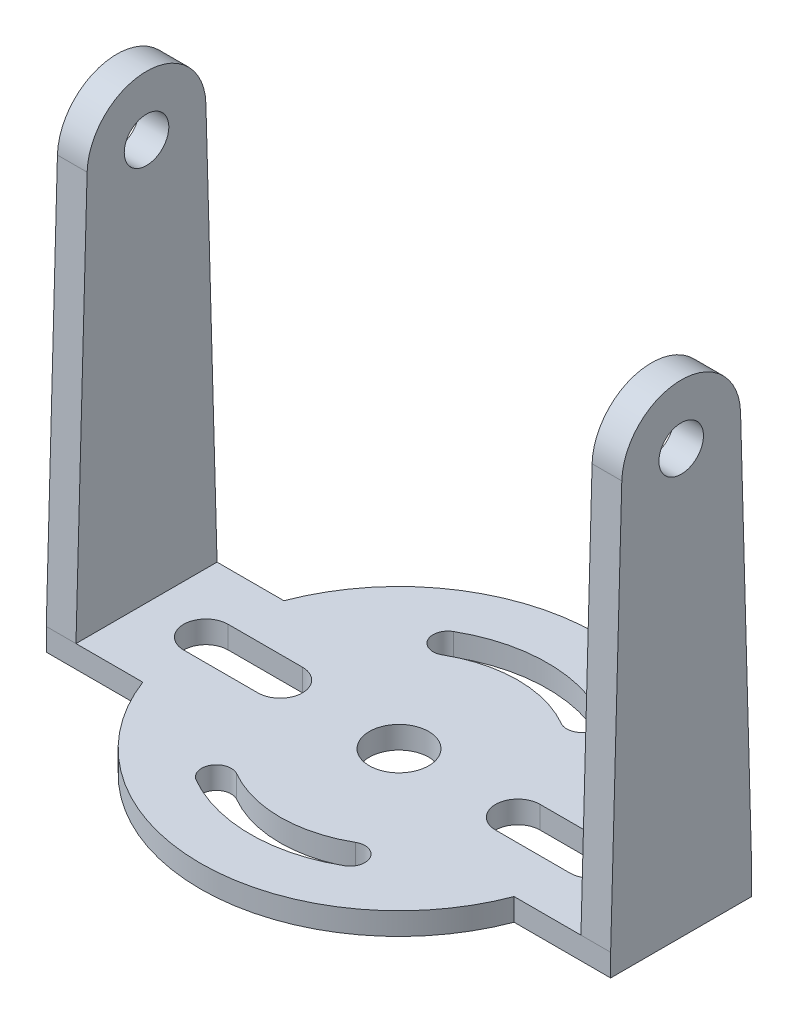
SolidWorks part; units mm, degrees
ref_plane "前视基准面" through (0, 0, 0) normal (0, 0, 1) x (1, 0, 0)
ref_plane "上视基准面" through (0, 0, 0) normal (0, 1, 0) x (1, 0, 0)
ref_plane "右视基准面" through (0, 0, 0) normal (1, 0, 0) x (0, 0, -1)
other "Configuration Table"
sketch "草图1" plane through (0, 0, 0) normal (1, 0, 0) x (0, 0, -1)
  line L0 (-3.9985, 0.1108) -> (-4.75, -27)
  line L1 (-4.75, -27) -> (4.75, -27)
  line L2 (4.75, -27) -> (3.9985, 0.1108)
  line L3 (0, -27) -> (0, -9.5695) construction
  arc A0 (3.9985, 0.1108) -> (-3.9985, 0.1108) centre (0, 0) ccw
  dimension "D1" = 4
  dimension "D2" = 9.5
  dimension "D3" = 27
extrude "凸台-拉伸1" add sketch "草图1" along normal blind 38
sketch "草图3" plane through (0, -27, 0) normal (0, -1, 0) x (1, 0, 0)
  line L5 (2, 4.75) -> (36, 4.75)
  line L6 (2, 4.75) -> (2, -4.75)
  line L7 (2, -4.75) -> (36, -4.75)
  line L14 (0, 4.75) -> (0, -4.75)
  line L15 (0, -4.75) -> (38, -4.75)
  line L16 (38, -4.75) -> (38, 4.75)
  line L17 (38, 4.75) -> (0, 4.75)
  line L18 (0, 4.75) -> (0, -4.75) construction
  line L19 (0, -4.75) -> (38, -4.75) construction
  line L20 (38, -4.75) -> (38, 4.75) construction
  line L21 (38, 4.75) -> (0, 4.75) construction
  line L22 (36, 4.75) -> (36, -4.75)
  dimension "D2" = 2
  dimension "D3" = 2
  dimension "D1" = 0
sketch "草图4" plane through (0, -27, 0) normal (0, -1, 0) x (1, 0, 0)
  line L0 (19, -13.3721) -> (19, -34.4064) construction
  line L1 (0, 0) -> (5.6279, 0) construction
  line L2 (6.5, 4.75) -> (0, 4.75)
  line L3 (38, 0) -> (43.8068, 0) construction
  line L4 (0, 4.75) -> (0, -4.75)
  line L5 (0, -4.75) -> (38, -4.75)
  line L6 (38, -4.75) -> (38, 4.75)
  line L7 (38, 4.75) -> (0, 4.75)
  line L8 (0, 4.75) -> (0, -4.75)
  line L9 (0, -4.75) -> (6.5, -4.75)
  line L10 (38, -4.75) -> (38, 4.75)
  line L11 (38, 4.75) -> (31.5, 4.75)
  line L12 (31.5, -4.75) -> (38, -4.75)
  line L14 (19, 4.75) -> (19, -19.4904) construction
  line L15 (38, 4.75) -> (0, 4.75) construction
  arc A0 (6.5, -4.75) -> (31.5, -4.75) centre (19, 0) ccw
  arc A1 (31.5, 4.75) -> (6.5, 4.75) centre (19, 0) ccw
  point P8 (6.5, 4.75)
  point P9 (6.5, 4.75)
  point P10 (31.5, 4.75)
  dimension "D2" = 25
  dimension "D1" = 0
extrude "凸台-拉伸2" add sketch "草图4" along normal blind 1.5
extrude "切除-拉伸1" cut sketch "草图3" against normal through all
sketch "草图6" plane through (0, -28.5, 0) normal (0, -1, 0) x (1, 0, 0)
  line L0 (-2.4396, 0) -> (43.8312, 0) construction
  line L1 (19, 8) -> (19, 0) construction
  line L2 (14.5, 7.7942) -> (19, 0) construction
  line L3 (19, 0) -> (23.5, 7.7942) construction
  line L4 (6, 1.5) -> (11, 1.5)
  line L5 (6, -1.5) -> (11, -1.5)
  line L6 (32, 1.5) -> (27, 1.5)
  line L7 (32, -1.5) -> (27, -1.5)
  arc A0 (31.5, 4.75) -> (6.5, 4.75) centre (19, 0) ccw construction
  arc A1 (31.5, 4.75) -> (6.5, 4.75) centre (19, 0) ccw construction
  arc A2 (24, 8.6603) -> (14, 8.6603) centre (19, 0) ccw
  arc A3 (23, 6.9282) -> (15, 6.9282) centre (19, 0) ccw
  arc A4 (14, 8.6603) -> (15, 6.9282) centre (14.5, 7.7942) ccw
  arc A5 (24, 8.6603) -> (23, 6.9282) centre (23.5, 7.7942) cw
  arc A6 (24, -8.6603) -> (23, -6.9282) centre (23.5, -7.7942) ccw
  arc A7 (24, -8.6603) -> (14, -8.6603) centre (19, 0) cw
  arc A8 (14, -8.6603) -> (15, -6.9282) centre (14.5, -7.7942) cw
  arc A9 (23, -6.9282) -> (15, -6.9282) centre (19, 0) cw
  circle A10 centre (19, 0) radius 2
  arc A11 (11, 1.5) -> (11, -1.5) centre (11, 0) cw
  arc A12 (6, 1.5) -> (6, -1.5) centre (6, 0) ccw
  arc A13 (32, 1.5) -> (32, -1.5) centre (32, 0) cw
  arc A14 (27, 1.5) -> (27, -1.5) centre (27, 0) ccw
  point P32 (10.8589, 0)
  point P33 (10.7147, 0)
  point P34 (11.3196, 0)
  point P35 (10.9091, 0)
  dimension "D1" = 10
  dimension "D2" = 8
  dimension "D3" = 60
  dimension "D4" = 4
  dimension "D5" = 3
  dimension "D6" = 5
  dimension "D7" = 13
extrude "切除-拉伸2" cut sketch "草图6" against normal up to surface (1.5 mm away) up to face at (19, -27, 0)
sketch "草图7" plane through (0, 0, 0) normal (-1, 0, 0) x (0, 0, 1)
  circle A0 centre (0, 0) radius 1.5
  dimension "D1" = 3
extrude "切除-拉伸3" cut sketch "草图7" against normal up to surface (38 mm away) up to face at (38, -17.8149, 0)
